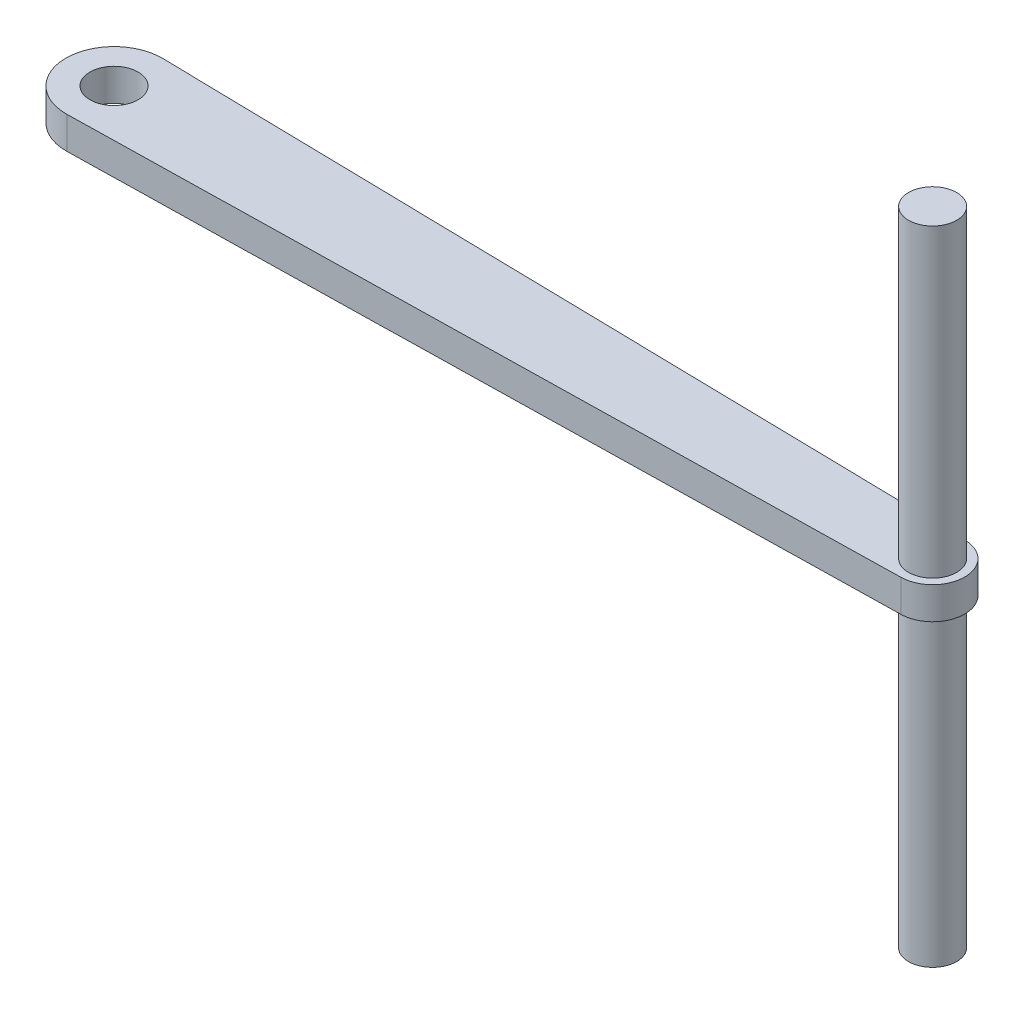
SolidWorks part; units mm, degrees
ref_plane "Front Plane" through (0, 0, 0) normal (0, 0, 1) x (1, 0, 0)
ref_plane "Top Plane" through (0, 0, 0) normal (0, 1, 0) x (1, 0, 0)
ref_plane "Right Plane" through (0, 0, 0) normal (1, 0, 0) x (0, 0, -1)
sketch "Sketch1" plane through (0, 0, 0) normal (0, 1, 0) x (1, 0, 0)
  circle A0 centre (0, 0) radius 1.5
  dimension "D1" = 3
extrude "Boss-Extrude1" add sketch "Sketch1" along normal mid plane 40
sketch "Sketch2" plane through (0, 0, 0) normal (0, 1, 0) x (1, 0, 0)
  line L0 (-29.7739, 0) -> (33.4446, 0) construction
  line L1 (-50.9412, 2.9994) -> (0.0392, 1.9996)
  line L2 (-50.9412, -2.9994) -> (0.0392, -1.9996)
  arc A2 (0.0392, -1.9996) -> (0.0392, 1.9996) centre (0, 0) ccw
  arc A3 (-50.9412, 2.9994) -> (-50.9412, -2.9994) centre (-51, 0) ccw
  circle A4 centre (-51, 0) radius 1.5
  point P2 (0, 0)
  dimension "D1" = 4
  dimension "D2" = 6
  dimension "D3" = 3
  dimension "D4" = 51
extrude "Boss-Extrude2" add sketch "Sketch2" along normal mid plane 2
